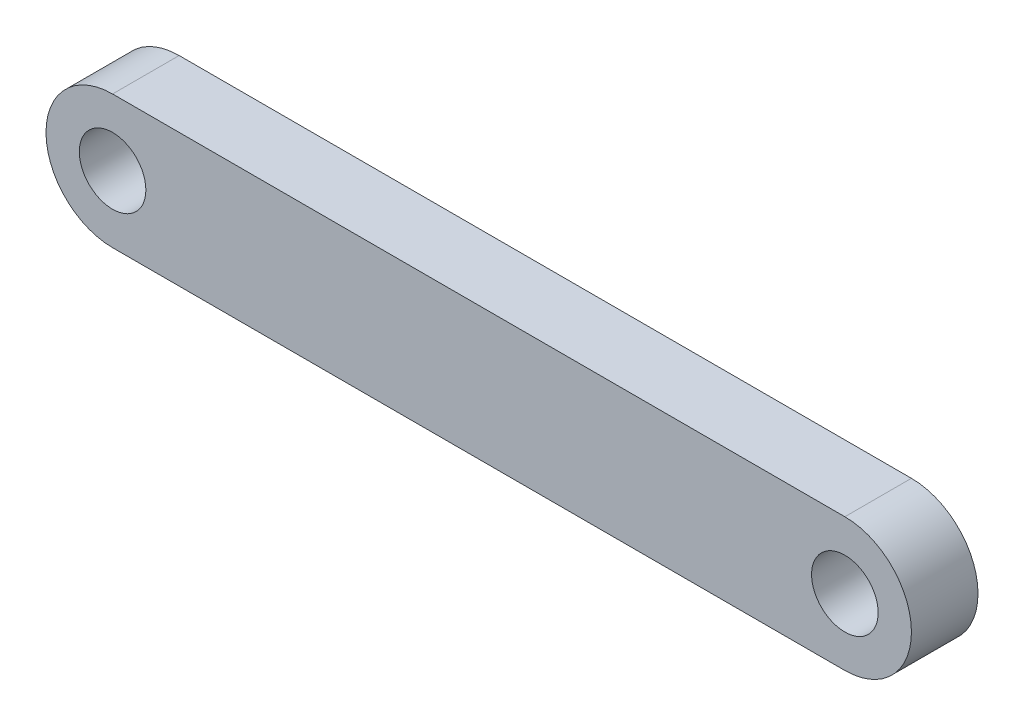
SolidWorks part; units mm, degrees
material "Thornel Mat VMA"
ref_plane "前视基准面" through (0, 0, 0) normal (0, 0, 1) x (1, 0, 0)
ref_plane "上视基准面" through (0, 0, 0) normal (0, 1, 0) x (1, 0, 0)
ref_plane "右视基准面" through (0, 0, 0) normal (1, 0, 0) x (0, 0, -1)
sketch "草图1" plane through (0, 0, 0) normal (0, 0, 1) x (1, 0, 0)
  line L0 (0, 0) -> (33, 0) construction
  line L2 (0, 3) -> (33, 3)
  line L3 (0, -3) -> (33, -3)
  arc A0 (0, 3) -> (0, -3) centre (0, 0) ccw
  arc A1 (33, -3) -> (33, 3) centre (33, 0) ccw
  circle A2 centre (0, 0) radius 1.5
  circle A3 centre (33, 0) radius 1.5
  point P5 (16.5, 0)
  dimension "D1" = 3
  dimension "D2" = 3
  dimension "D3" = 3
  dimension "D4" = 33
extrude "凸台-拉伸1" add sketch "草图1" along normal blind 3
